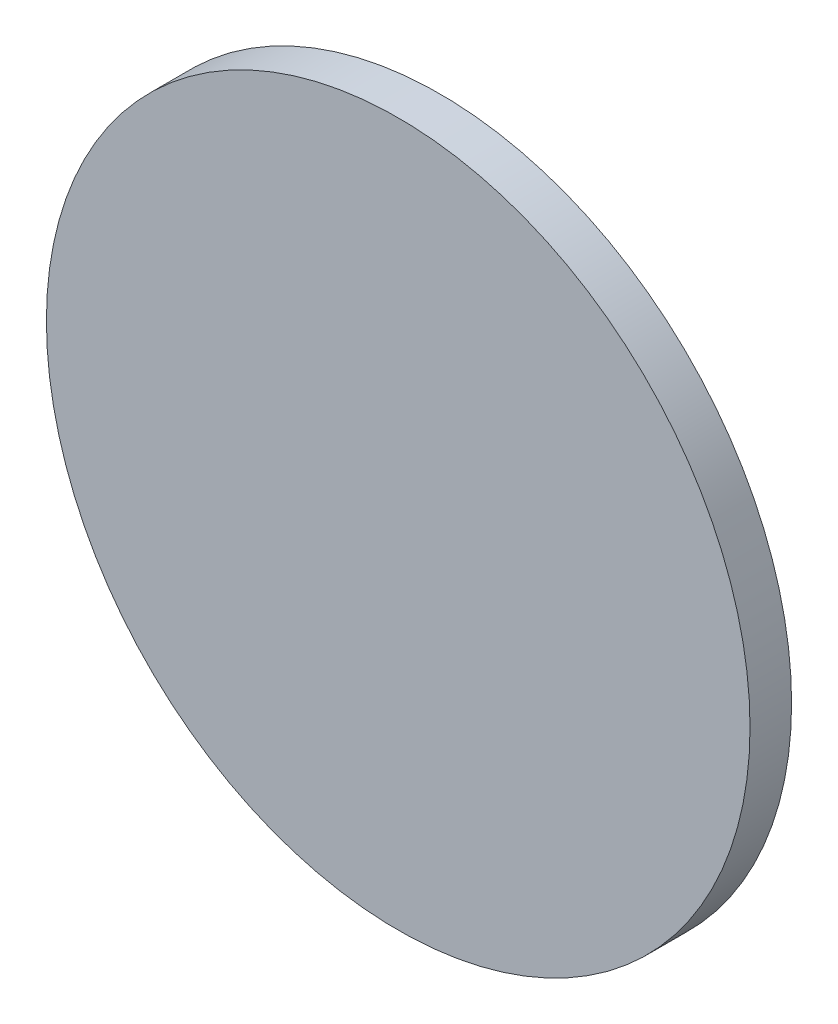
SolidWorks part; units mm, degrees
ref_plane "Front Plane" through (0, 0, 0) normal (0, 0, 1) x (1, 0, 0)
ref_plane "Top Plane" through (0, 0, 0) normal (0, 1, 0) x (1, 0, 0)
ref_plane "Right Plane" through (0, 0, 0) normal (1, 0, 0) x (0, 0, -1)
sketch "Sketch1" plane through (0, 0, 0) normal (0, 0, 1) x (1, 0, 0)
  circle A0 centre (0, 0) radius 25.4
  dimension "D1" = 50.8
extrude "Boss-Extrude1" add sketch "Sketch1" along normal blind 3
